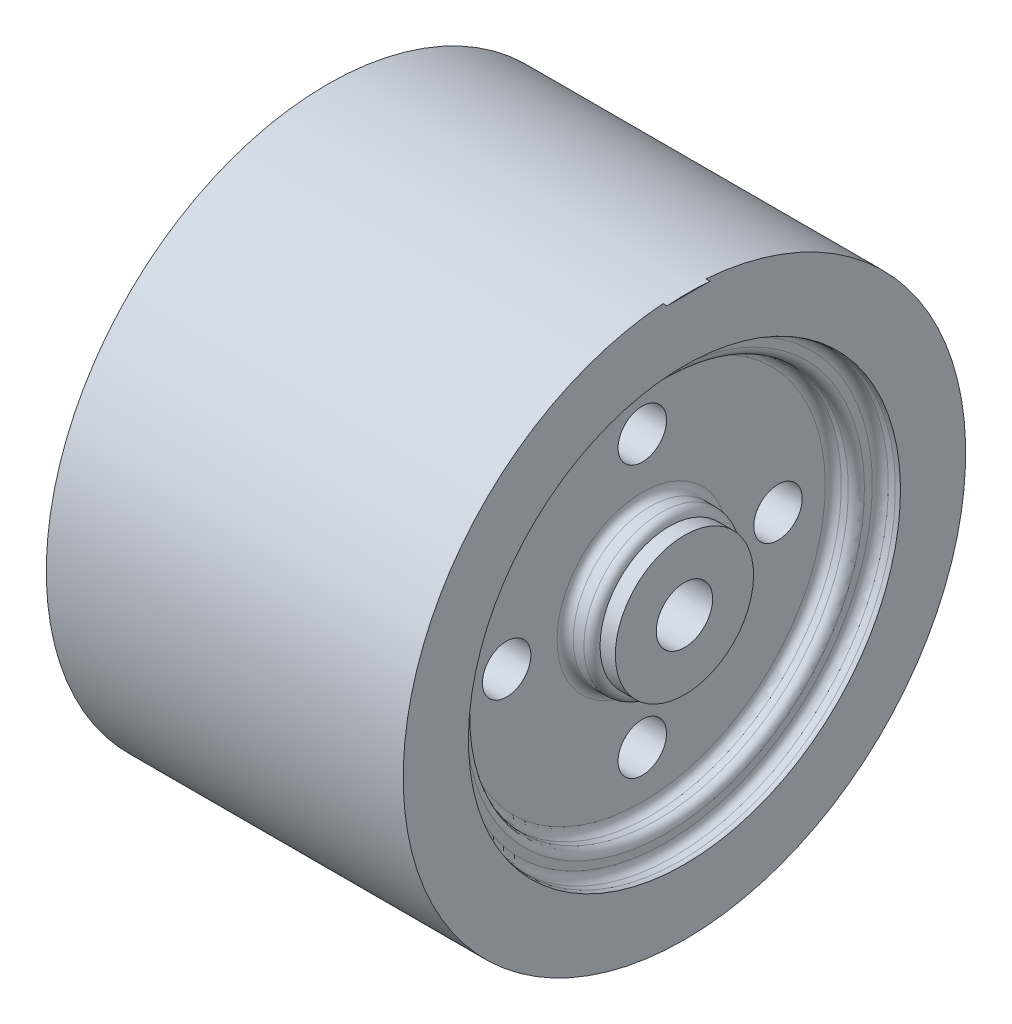
SolidWorks part; units mm, degrees
ref_plane "Front Plane" through (0, 0, 0) normal (0, 0, 1) x (1, 0, 0)
ref_plane "Top Plane" through (0, 0, 0) normal (0, 1, 0) x (1, 0, 0)
ref_plane "Right Plane" through (0, 0, 0) normal (1, 0, 0) x (0, 0, -1)
sketch "Sketch1" plane through (0, 0, 0) normal (0, 0, 1) x (1, 0, 0)
  line L0 (0, 67.0783) -> (0, 30.585) construction
  line L1 (0, -58.1203) -> (-71.6872, -4.415) construction
  line L2 (-71.6872, -4.415) -> (75.9784, -4.415) construction
  line L3 (20, 30.585) -> (-20, 30.585)
  line L4 (-20, 30.585) -> (-20, 25.506)
  line L5 (-19, 24.506) -> (-17.6686, 24.506)
  line L6 (-16.6686, 23.506) -> (-16.6686, 11.3752)
  line L7 (-20.5343, 7.4032) -> (-21.4, 7.4032)
  line L10 (-19.5343, 8.4032) -> (-19.5343, 9.3752)
  line L11 (-18.5343, 10.3752) -> (-17.6686, 10.3752)
  line L12 (-45.345, 34.085) -> (44.7475, 34.085) construction
  line L13 (18.5343, 10.3752) -> (17.6686, 10.3752)
  line L14 (19.5343, 8.4032) -> (19.5343, 9.3752)
  line L16 (20.5343, 7.4032) -> (21.4, 7.4032)
  line L17 (16.6686, 23.506) -> (16.6686, 11.3752)
  line L18 (19, 24.506) -> (17.6686, 24.506)
  line L19 (20, 30.585) -> (20, 25.506)
  line L20 (0, -4.415) -> (0, -58.1203) construction
  line L21 (-22.4, 6.4032) -> (-22.4, -0.8224)
  line L22 (-22.4, -0.8224) -> (22.4, -0.8224)
  line L23 (22.4, -0.8224) -> (22.4, 6.4032)
  arc A0 (-21.4, 7.4032) -> (-22.4, 6.4032) centre (-21.4, 6.4032) ccw
  arc A1 (-19.5343, 8.4032) -> (-20.5343, 7.4032) centre (-20.5343, 8.4032) cw
  arc A2 (-19.5343, 9.3752) -> (-18.5343, 10.3752) centre (-18.5343, 9.3752) cw
  arc A3 (-17.6686, 10.3752) -> (-16.6686, 11.3752) centre (-17.6686, 11.3752) ccw
  arc A4 (-17.6686, 24.506) -> (-16.6686, 23.506) centre (-17.6686, 23.506) cw
  arc A5 (-20, 25.506) -> (-19, 24.506) centre (-19, 25.506) ccw
  arc A6 (20, 25.506) -> (19, 24.506) centre (19, 25.506) cw
  arc A7 (17.6686, 24.506) -> (16.6686, 23.506) centre (17.6686, 23.506) ccw
  arc A8 (17.6686, 10.3752) -> (16.6686, 11.3752) centre (17.6686, 11.3752) cw
  arc A9 (19.5343, 9.3752) -> (18.5343, 10.3752) centre (18.5343, 9.3752) ccw
  arc A10 (19.5343, 8.4032) -> (20.5343, 7.4032) centre (20.5343, 8.4032) ccw
  arc A11 (21.4, 7.4032) -> (22.4, 6.4032) centre (21.4, 6.4032) cw
  dimension "D5" = 1
  dimension "D1" = 20
  dimension "D2" = 35
  dimension "D3" = 44.8
  dimension "D6" = 3.5
revolve "Revolve2" add sketch "Sketch1" angle 360 about L12
sketch "Sketch4" plane through (16.6686, 0, 0) normal (1, 0, 0) x (0, 0, -1)
  circle A0 centre (0, 50.9245) radius 3.0073
  circle A1 centre (16.8394, 34.085) radius 3.0073
  circle A2 centre (0, 17.2456) radius 3.0073
  circle A3 centre (-16.8394, 34.085) radius 3.0073
  point P11 (0, 34.085)
  dimension "D1" = 4
extrude "Cut-Extrude2" cut sketch "Sketch4" against normal blind 67
sketch "Sketch5" plane through (20, 0, 0) normal (1, 0, 0) x (0, 0, -1)
  circle A0 centre (0, 34.085) radius 8.5791
  circle A1 centre (0, 34.085) radius 3.5
extrude "Boss-Extrude1" add sketch "Sketch5" against normal blind 44 and the other way blind 4
sketch "Sketch6" plane through (-24, 0, 0) normal (-1, 0, 0) x (0, 0, 1)
  line L1 (12.301, 42.5537) -> (-15.1719, 42.5537)
  line L2 (12.301, 42.5537) -> (12.301, 21.419)
  line L3 (12.301, 21.419) -> (-15.1719, 21.419)
  line L4 (-15.1719, 42.5537) -> (-15.1719, 21.419)
extrude "Cut-Extrude3" cut sketch "Sketch6" against normal blind 2
sketch "Sketch7" plane through (24, 0, 0) normal (1, 0, 0) x (0, 0, -1)
  line L1 (-14.8963, 46.1092) -> (12.7544, 46.1092)
  line L2 (-14.8963, 46.1092) -> (-14.8963, 22.4503)
  line L3 (-14.8963, 22.4503) -> (12.7544, 22.4503)
  line L4 (12.7544, 46.1092) -> (12.7544, 22.4503)
extrude "Cut-Extrude4" cut sketch "Sketch7" against normal blind 2
sketch "Sketch8" plane through (22.4, 0, 0) normal (1, 0, 0) x (0, 0, -1)
  line L1 (-46.8309, 68.8918) -> (58.9037, 68.8918)
  line L2 (-46.8309, 68.8918) -> (-46.8309, -5.2003)
  line L3 (-46.8309, -5.2003) -> (58.9037, -5.2003)
  line L4 (58.9037, 68.8918) -> (58.9037, -5.2003)
extrude "Cut-Extrude5" cut sketch "Sketch8" against normal blind 0.5
sketch "Sketch9" plane through (-22, 0, 0) normal (-1, 0, 0) x (0, 0, 1)
  line L1 (-12.8517, 45.8171) -> (16.9409, 45.8171)
  line L2 (-12.8517, 45.8171) -> (-12.8517, 21.3794)
  line L3 (-12.8517, 21.3794) -> (16.9409, 21.3794)
  line L4 (16.9409, 45.8171) -> (16.9409, 21.3794)
extrude "Cut-Extrude7" cut sketch "Sketch9" along normal blind 16.5
